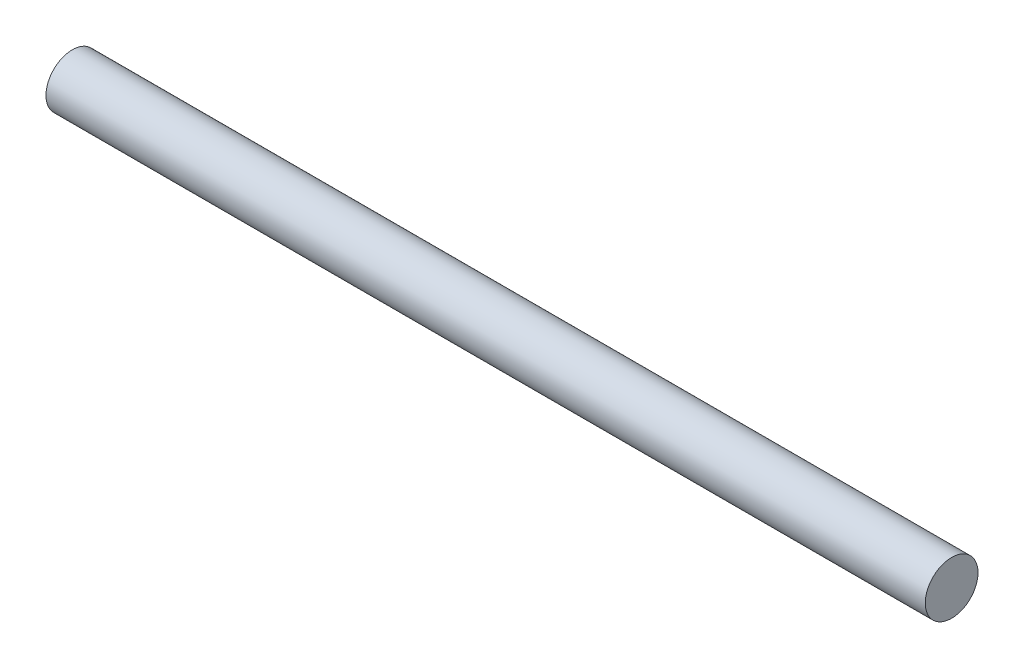
SolidWorks part; units mm, degrees
ref_plane "Front" through (0, 0, 0) normal (0, 0, 1) x (1, 0, 0)
ref_plane "Top" through (0, 0, 0) normal (0, 1, 0) x (1, 0, 0)
ref_plane "Right" through (0, 0, 0) normal (1, 0, 0) x (0, 0, -1)
sketch "Эскиз1" plane through (0, 0, 0) normal (1, 0, 0) x (0, 0, -1)
  circle A0 centre (0, 0) radius 0.3
extrude "Бобышка-Вытянуть1" add sketch "Эскиз1" along normal blind 10
